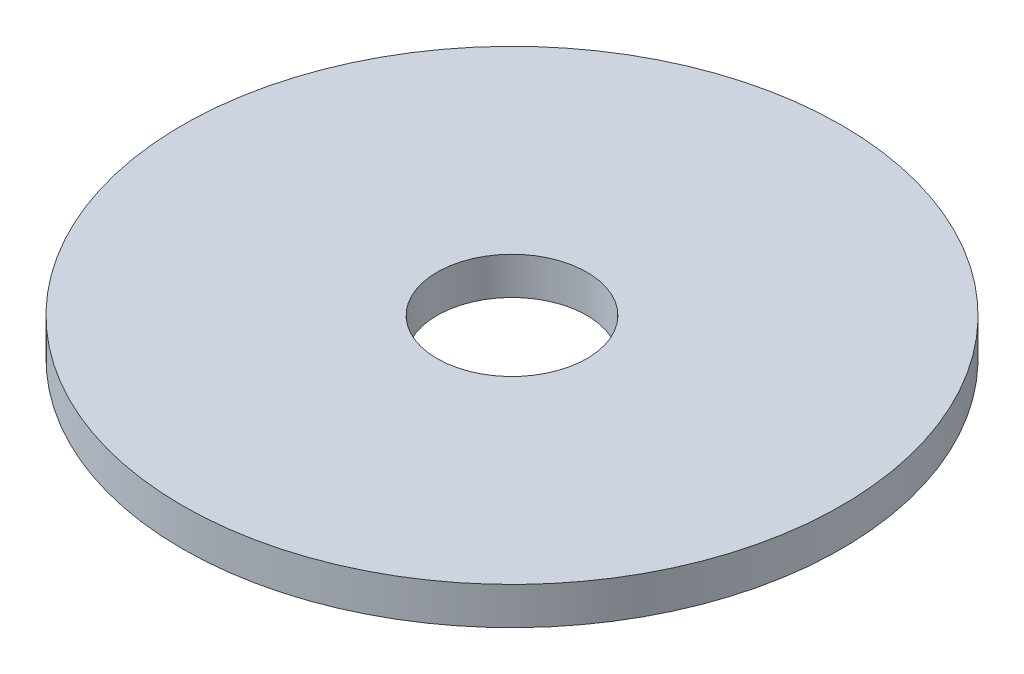
SolidWorks part; units mm, degrees
ref_plane "Front Plane" through (0, 0, 0) normal (0, 0, 1) x (1, 0, 0)
ref_plane "Top Plane" through (0, 0, 0) normal (0, 1, 0) x (1, 0, 0)
ref_plane "Right Plane" through (0, 0, 0) normal (1, 0, 0) x (0, 0, -1)
sketch "Sketch1" plane through (0, 0, 0) normal (0, 1, 0) x (1, 0, 0)
  circle A0 centre (0, 0) radius 27.94
  dimension "D1" = 55.88
extrude "Boss-Extrude1" add sketch "Sketch1" along normal blind 3.175
sketch "Sketch2" plane through (0, 3.175, 0) normal (0, 1, 0) x (1, 0, 0)
  circle A0 centre (0, 0) radius 6.35
  dimension "D1" = 12.7
extrude "Cut-Extrude1" cut sketch "Sketch2" against normal through all
